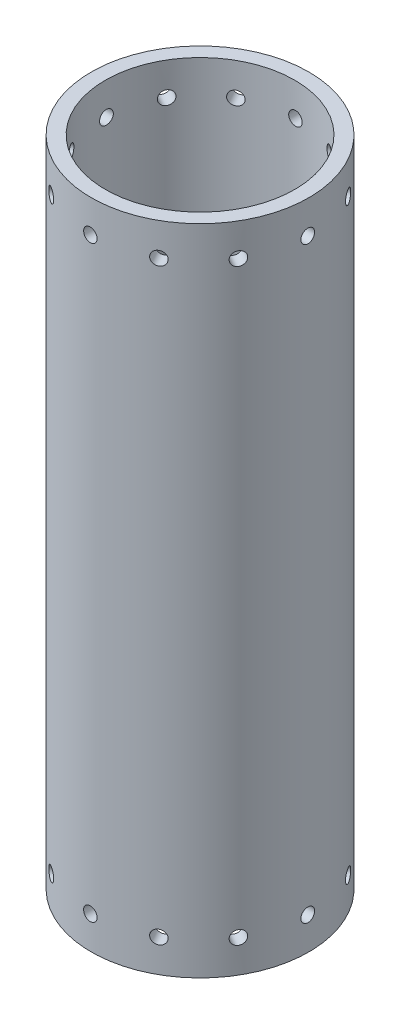
SolidWorks part; units mm, degrees
ref_plane "Front Plane" through (0, 0, 0) normal (0, 0, 1) x (1, 0, 0)
ref_plane "Top Plane" through (0, 0, 0) normal (0, 1, 0) x (1, 0, 0)
ref_plane "Right Plane" through (0, 0, 0) normal (1, 0, 0) x (0, 0, -1)
sketch "Sketch1" plane through (0, 0, 0) normal (0, 0, 1) x (1, 0, 0)
  line L0 (0, 0) -> (0, 304.8) construction
  line L4 (50.8, 0) -> (50.8, 304.8)
  line L5 (50.8, 0) -> (44.196, 0)
  line L6 (44.196, 0) -> (44.196, 304.8)
  line L7 (44.196, 304.8) -> (50.8, 304.8)
  dimension "D1" = 304.8
  dimension "D2" = 50.8
  dimension "D3" = 6.604
revolve "Revolve1" add sketch "Sketch1" angle 360 about L0
hole_wizard "E (0.25) Diameter Hole1" positions "3DSketch2" profile "Sketch3" hole size "E" standard "ANSI Inch"
sketch3d "3DSketch2"
  point P0 (44.23, 289.56, -24.987)
  point P6 (0, 0, 0)
  point P7 (0, 0, 0)
  point P8 (0, 0, 0)
  dimension "D1" = 15.24
sketch "Sketch3" plane through (44.23, 289.56, -24.987) normal (0, 1, 0) x (-0.4919, 0, -0.8707)
  line L0 (0, 0) -> (0, 52.7067)
  line L1 (0, 52.7067) -> (3.175, 50.799)
  line L2 (3.175, 50.799) -> (3.175, 0)
  line L5 (3.175, 0) -> (0, 0)
  line L10 (0, 52.7067) -> (-3.175, 50.799) construction
  line L11 (0, -6.35) -> (0, 107.95) construction
  dimension "Hole Dia." = 6.35
  dimension "Hole Depth" = 50.799
  dimension "Drill Angle" = 118
pattern_circular "CirPattern1" count 12 over 360 about axis through (0, 304.8, 0) along (0, -1, 0) of "E (0.25) Diameter Hole1"
pattern_linear "LPattern1" count 2 spacing 274.32 along (0, -1, 0) of "CirPattern1", "E (0.25) Diameter Hole1"
